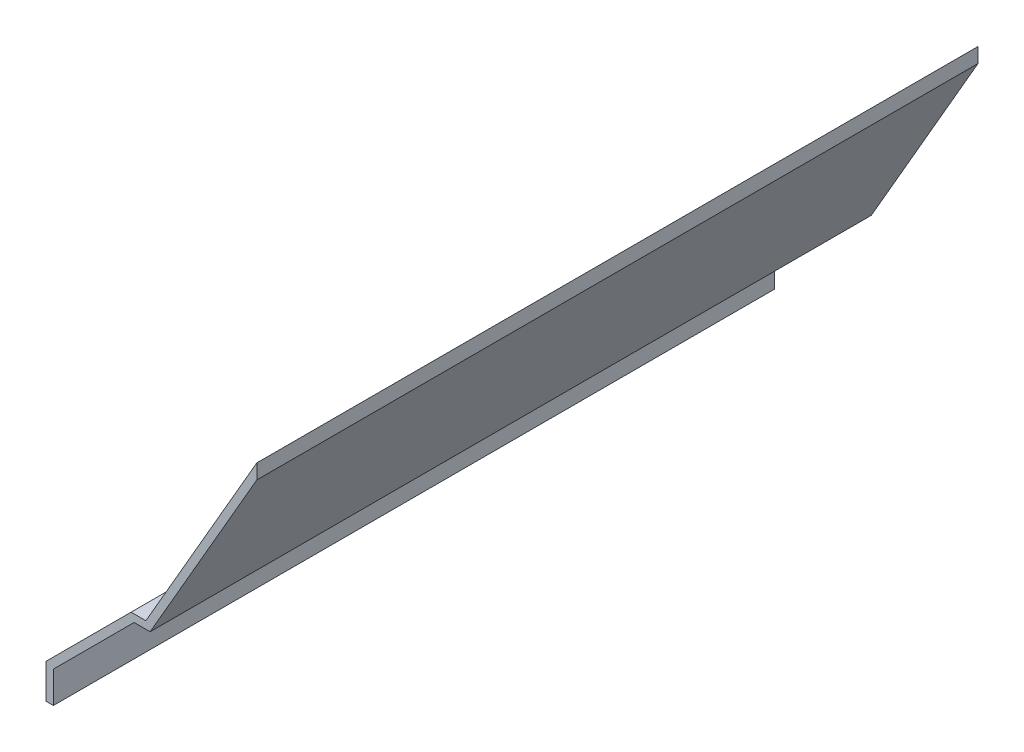
SolidWorks part; units mm, degrees
material "Plain Carbon Steel"
ref_plane "Front Plane" through (0, 0, 0) normal (0, 0, 1) x (1, 0, 0)
ref_plane "Top Plane" through (0, 0, 0) normal (0, 1, 0) x (1, 0, 0)
ref_plane "Right Plane" through (0, 0, 0) normal (1, 0, 0) x (0, 0, -1)
sketch "Sketch1" plane through (0, 0, 0) normal (0, 0, 1) x (1, 0, 0)
  line L0 (-49.8881, 168.4207) -> (-49.8881, 164.4207)
  line L1 (-106.8881, 84.1039) -> (-106.8881, 93.4592)
  line L4 (-106.8881, 93.4592) -> (-83.8881, 116.4592)
  line L5 (-83.8881, 116.4592) -> (-79.8881, 116.4592)
  line L6 (-79.8881, 116.4592) -> (-49.8881, 168.4207)
  line L7 (-104.8881, 84.1039) -> (-104.8881, 92.6308)
  line L8 (-104.8881, 92.6308) -> (-83.0597, 114.4592)
  line L9 (-83.0597, 114.4592) -> (-78.7334, 114.4592)
  line L10 (-78.7334, 114.4592) -> (-49.8881, 164.4207)
  line L11 (-106.8881, 84.1039) -> (-104.8881, 84.1039)
  line L13 (-78.7334, 114.4592) -> (-48.1561, 167.4207) construction
  dimension "D1" = 2
extrude "Boss-Extrude1" add sketch "Sketch1" along normal blind 195
